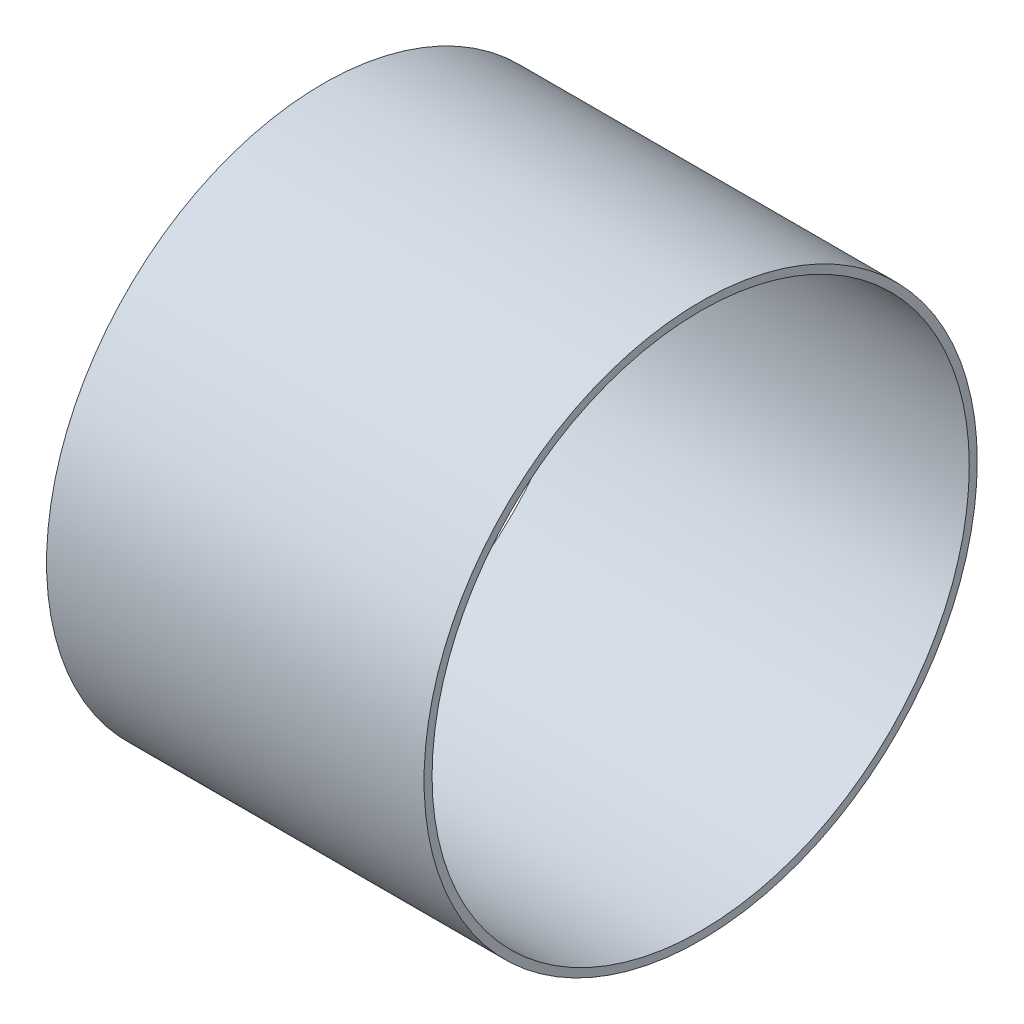
SolidWorks part; units mm, degrees
ref_plane "Front Plane" through (0, 0, 0) normal (0, 0, 1) x (1, 0, 0)
ref_plane "Top Plane" through (0, 0, 0) normal (0, 1, 0) x (1, 0, 0)
ref_plane "Right Plane" through (0, 0, 0) normal (1, 0, 0) x (0, 0, -1)
sketch "Sketch1" plane through (0, 0, 0) normal (1, 0, 0) x (0, 0, -1)
  circle A0 centre (0, 0) radius 57.15
  circle A1 centre (0, 0) radius 55.499
  dimension "D1" = 1.651
  dimension "D2" = 114.3
extrude "Boss-Extrude1" add sketch "Sketch1" along normal blind 78
